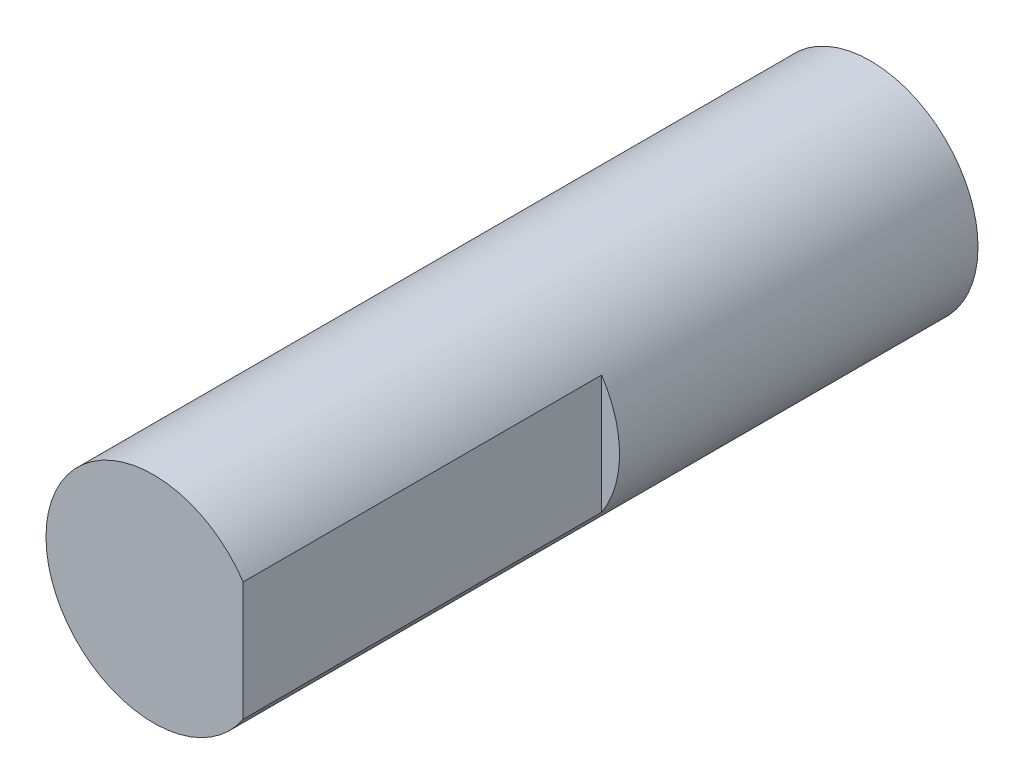
SolidWorks part; units mm, degrees
ref_plane "Frontal Plane" through (0, 0, 0) normal (0, 0, 1) x (1, 0, 0)
ref_plane "Horizontal Plane" through (0, 0, 0) normal (0, 1, 0) x (1, 0, 0)
ref_plane "Profile Plane" through (0, 0, 0) normal (1, 0, 0) x (0, 0, -1)
sketch "Sketch1" plane through (0, 0, 0) normal (0, 0, 1) x (1, 0, 0)
  circle A0 centre (0, 0) radius 3
  dimension "D1" = 6
extrude "Boss-Extrude1" add sketch "Sketch1" along normal blind 20
sketch "Sketch2" plane through (0, 0, 20) normal (0, 0, 1) x (1, 0, 0)
  line L0 (2.5, 1.6583) -> (2.5, -1.6583)
  circle A0 centre (0, 0) radius 3 construction
  arc A1 (2.5, 1.6583) -> (2.5, -1.6583) centre (0, 0) cw
  dimension "D1" = 2.5
extrude "Cut-Extrude1" cut sketch "Sketch2" against normal blind 10
equation "\"BaseL\"= 6ft"
equation "\"BaseW\"= 5.5in"
equation "\"BaseThickness\"= 1in"
equation "\"RailGap\"= 4cm"
equation "\"SlidePlateL\"= 8cm"
equation "\"SlidePlateW\"= 11cm"
equation "\"SlidePlateThickness\"= 5mm"
equation "\"SlidePlateClearance\"= 1cm"
equation "\"BoxThickness\"= .5cm"
equation "\"BoxX\"= \"RailGap\" + 30mm"
equation "\"BoxH\"= 2cm + \"SlidePlateClearance\" + \"SlidePlateThickness\" + 3cm"
equation "\"PulleyRadius\"= 15.1mm"
equation "\"PulleyH\"= 30mm + 21.4056mm - 2.5mm"
equation "\"PulleyShaftDiameter\"= .3125in"
equation "\"PulleyShaftL\"= 4in"
equation "\"PulleyShaft2L\"= 3in"
equation "\"MotorL\"= 4.43in"
equation "\"MotorRadius\"= 1.291in"
equation "\"MotorShaftRadius\"= .15625in"
equation "\"MotorShaftL\"= 1.75in"
equation "\"HeadstoneThickness\"= 7.5mm"
equation "\"BeltL\"= 1500mm + \"80\""
equation "\"BeltThickness\"= 2.5mm"
equation "\"BeltW\"= .375in"
equation "\"BeltLockH\"= \"PulleyH\" + 19.4056mm - (\"SlidePlateThickness\" + \"SlidePlateClearance\" + 15mm + 5mm)"
equation "\"EncoderL\"= 33mm"
equation "\"EncoderRadius\"= 19mm"
equation "\"EncoderShaftRadius\"= 3mm"
equation "\"EncoderShaftL\"= 15mm"
equation "\"D1@Sketch1\"=\"EncoderShaftRadius\"*2"
equation "\"D1@Boss-Extrude1\"=\"EncoderShaftL\"+5"
